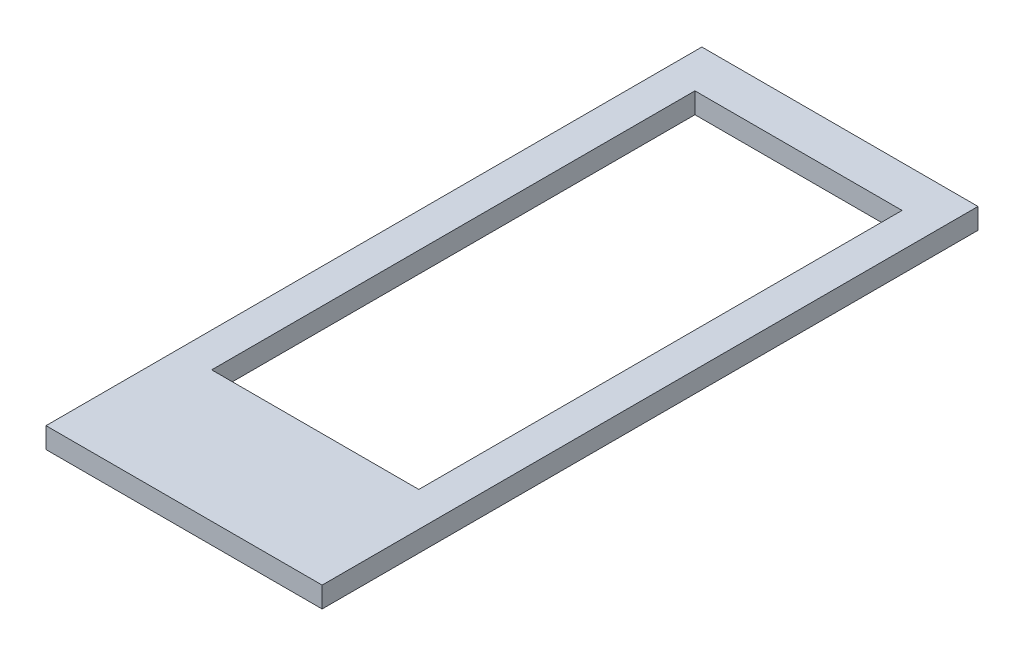
SolidWorks part; units mm, degrees
material "MDF"
ref_plane "Alzado" through (0, 0, 0) normal (0, 0, 1) x (1, 0, 0)
ref_plane "Planta" through (0, 0, 0) normal (0, 1, 0) x (1, 0, 0)
ref_plane "Vista lateral" through (0, 0, 0) normal (1, 0, 0) x (0, 0, -1)
sketch "Croquis2" plane through (0, 0, 0) normal (0, 1, 0) x (1, 0, 0)
  line L1 (-20, 47.5) -> (20, 47.5)
  line L2 (-20, 47.5) -> (-20, -47.5)
  line L3 (-20, -47.5) -> (20, -47.5)
  line L4 (20, 47.5) -> (20, -47.5)
  line L5 (-20, 47.5) -> (20, -47.5) construction
  line L6 (-20, -47.5) -> (20, 47.5) construction
  line L7 (-15, 41.5) -> (15, 41.5)
  line L8 (-15, 41.5) -> (-15, -28.5)
  line L9 (-15, -28.5) -> (15, -28.5)
  line L10 (15, 41.5) -> (15, -28.5)
  point P0 (0, 0)
  dimension "D1" = 40
  dimension "D2" = 95
  dimension "D3" = 70
  dimension "D4" = 5
  dimension "D5" = 5
  dimension "D6" = 6
extrude "Saliente-Extruir1" add sketch "Croquis2" along normal blind 3
